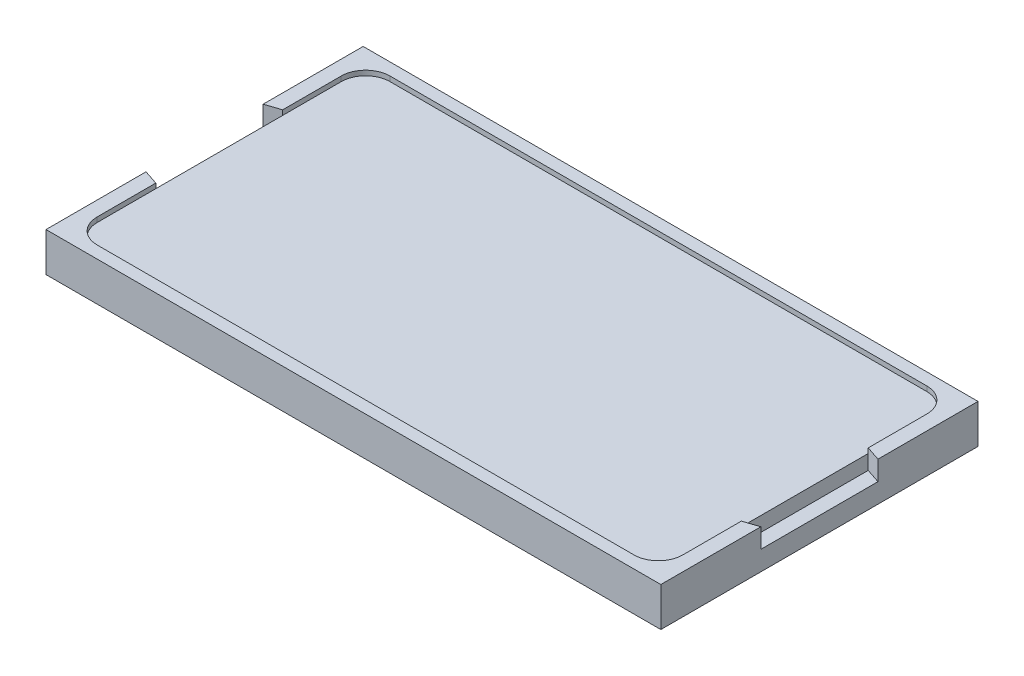
SolidWorks part; units mm, degrees
ref_plane "Front Plane" through (0, 0, 0) normal (0, 0, 1) x (1, 0, 0)
ref_plane "Top Plane" through (0, 0, 0) normal (0, 1, 0) x (1, 0, 0)
ref_plane "Right Plane" through (0, 0, 0) normal (1, 0, 0) x (0, 0, -1)
sketch "Sketch5" plane through (0, 0, 0) normal (0, 1, 0) x (1, 0, 0)
  line L1 (-800.1, 412.75) -> (800.1, 412.75)
  line L2 (-800.1, 412.75) -> (-800.1, -412.75)
  line L3 (-800.1, -412.75) -> (800.1, -412.75)
  line L4 (800.1, 412.75) -> (800.1, -412.75)
  line L5 (-800.1, 412.75) -> (800.1, -412.75) construction
  line L6 (-800.1, -412.75) -> (800.1, 412.75) construction
  point P0 (0, 0)
  dimension "D1" = 825.5
  dimension "D2" = 1600.2
extrude "Boss-Extrude1" add sketch "Sketch5" along normal blind 101.6
sketch "Sketch6" plane through (0, 101.6, 0) normal (0, 1, 0) x (1, 0, 0)
  line L1 (-762, 381) -> (762, 381)
  line L2 (-762, 381) -> (-762, -381)
  line L3 (-762, -381) -> (762, -381)
  line L4 (762, 381) -> (762, -381)
  line L5 (-762, 381) -> (762, -381) construction
  line L6 (-762, -381) -> (762, 381) construction
  point P0 (0, 0)
  dimension "D1" = 762
  dimension "D2" = 1524
extrude "Cut-Extrude1" cut sketch "Sketch6" against normal blind 12.7 contours L3 L4 L1 L2
sketch "Sketch10" plane through (0, 101.6, 0) normal (0, 1, 0) x (1, 0, 0)
  line L1 (800.1, -152.4) -> (800.1, 0)
  line L4 (800.1, -412.75) -> (800.1, 412.75) construction
  line L9 (800.1, 0) -> (800.1, 152.4)
  line L10 (762, -165.1) -> (800.1, -152.4)
  line L13 (762, 165.1) -> (800.1, 152.4)
  line L17 (762, 0) -> (762, -165.1)
  line L18 (762, 381) -> (762, -381) construction
  line L19 (762, 0) -> (762, 165.1)
  line L20 (762, 381) -> (762, -381) construction
extrude "Cut-Extrude2" cut sketch "Sketch10" against normal blind 50.8 contours L9 L13 L19 L17 L10 L1
sketch "Sketch12" plane through (0, 101.6, 0) normal (0, 1, 0) x (1, 0, 0)
  line L0 (-800.1, 0) -> (-800.1, 152.4)
  line L1 (-800.1, 412.75) -> (-800.1, -412.75) construction
  line L2 (-800.1, 0) -> (-800.1, -152.4)
  line L3 (-762, 0) -> (-762, 165.1)
  line L4 (-762, 381) -> (-762, -381) construction
  line L5 (-762, 0) -> (-762, -165.1)
  line L6 (-800.1, -152.4) -> (-762, -165.1)
  line L7 (-800.1, 152.4) -> (-762, 165.1)
extrude "Cut-Extrude3" cut sketch "Sketch12" against normal up to vertex (50.8 mm away) up to point (800.1, 50.8, -152.4)
sketch "Sketch14" plane through (0, 88.9, 0) normal (0, 1, 0) x (1, 0, 0)
  line L0 (762, 165.1) -> (762, 152.2573)
  line L1 (762.1427, -165.3855) -> (762.1427, -152.5428)
  line L2 (-762, -381) -> (762, -381) construction
  line L3 (-762, 165.1) -> (-762, 152.4)
  line L4 (-762, -165.1) -> (-762, -152.4)
  line L5 (6.35, 381) -> (-6.35, 381)
  line L6 (6.35, 381) -> (6.35, -381)
  line L7 (6.35, -381) -> (-6.35, -381)
  line L8 (-6.35, 381) -> (-6.35, -381)
  line L9 (6.35, 381) -> (-6.35, -381) construction
  line L10 (6.35, -381) -> (-6.35, 381) construction
  arc A0 (762, 165.1) -> (762.1427, -165.3855) centre (762.1427, -0.1427) ccw
  arc A1 (762, 152.2573) -> (762.1427, -152.5428) centre (762.1427, -0.1427) ccw
  arc A2 (-762, 152.4) -> (-762, -152.4) centre (-762, 0) cw
  arc A3 (-762, 165.1) -> (-762, -165.1) centre (-762, 0) cw
  point P3 (0, 0)
  dimension "D1" = 762
sketch "Sketch15" plane through (0, 88.9, 0) normal (0, 1, 0) x (1, 0, 0)
  circle A0 centre (0, 0) radius 165.1
  circle A1 centre (0, 0) radius 152.4
  dimension "D1" = 330.2
  dimension "D2" = 304.8
sketch "Sketch16" plane through (0, 88.9, 0) normal (0, 1, 0) x (1, 0, 0)
  line L0 (762, 381) -> (762, 317.5)
  line L1 (762, 317.5) -> (762, 381)
  line L3 (-762, -381) -> (762, -381) construction
  line L4 (762, 381) -> (762, 165.1) construction
  line L5 (762, 381) -> (762, 165.1) construction
  line L6 (762, 381) -> (698.5, 381)
  line L7 (-762, 317.5) -> (-762, 381)
  line L8 (-762, 381) -> (-698.5, 381)
  line L9 (-698.5, -381) -> (-762, -381)
  line L10 (-762, -381) -> (-762, -317.5)
  line L11 (698.5, -381) -> (762, -381)
  line L12 (762, -381) -> (762, -317.5)
  arc A0 (-698.5, -381) -> (-762, -317.5) centre (-698.5, -317.5) cw
  arc A1 (-698.5, 381) -> (-762, 317.5) centre (-698.5, 317.5) ccw
  arc A2 (698.5, 381) -> (762, 317.5) centre (698.5, 317.5) cw
  arc A3 (698.5, -381) -> (762, -317.5) centre (698.5, -317.5) ccw
extrude "Boss-Extrude4" add sketch "Sketch16" along normal blind 12.7 contours L10 A0 L9 | L7 L8 A1 | A2 L6 L0 | L12 A3 L11
